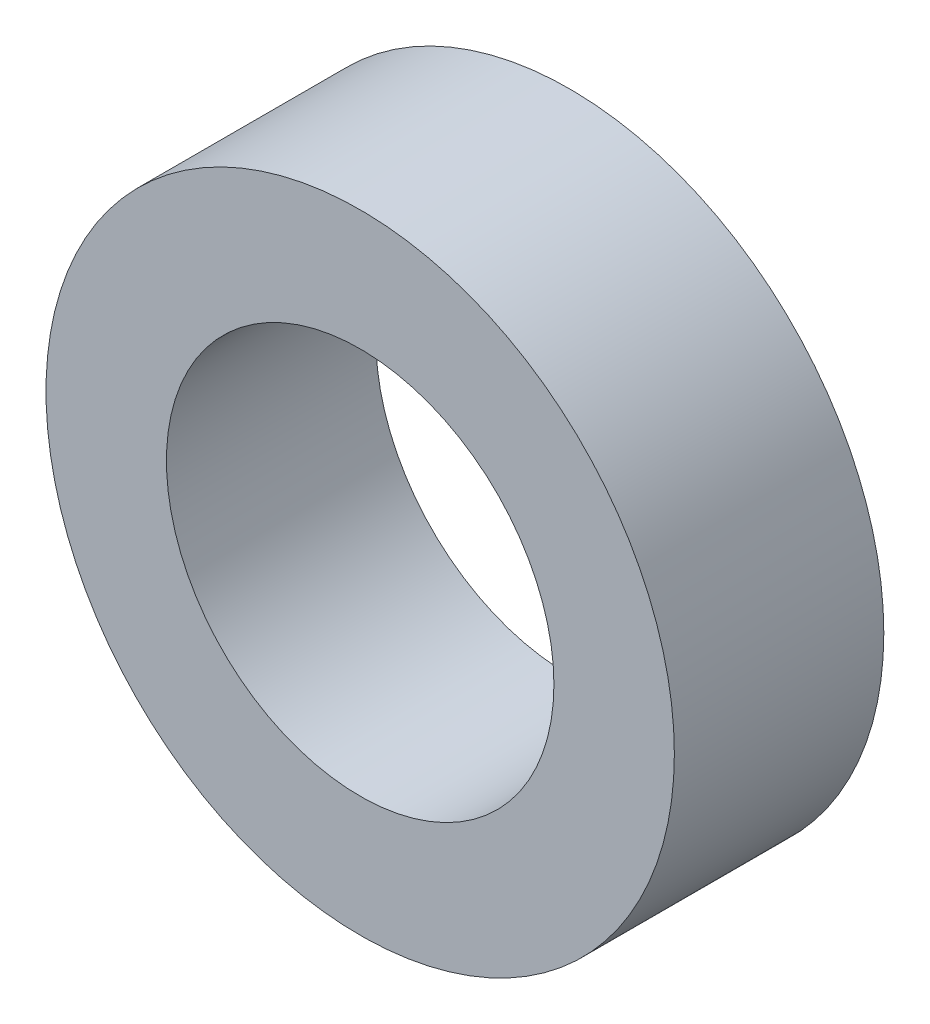
SolidWorks part; units mm, degrees
ref_plane "Front Plane" through (0, 0, 0) normal (0, 0, 1) x (1, 0, 0)
ref_plane "Top Plane" through (0, 0, 0) normal (0, 1, 0) x (1, 0, 0)
ref_plane "Right Plane" through (0, 0, 0) normal (1, 0, 0) x (0, 0, -1)
sketch "Sketch1" plane through (0, 0, 0) normal (0, 0, 1) x (1, 0, 0)
  circle A0 centre (0, 0) radius 1.85
  circle A1 centre (0, 0) radius 3
  dimension "D1" = 3.7
  dimension "D2" = 6
extrude "Boss-Extrude1" add sketch "Sketch1" along normal blind 2
